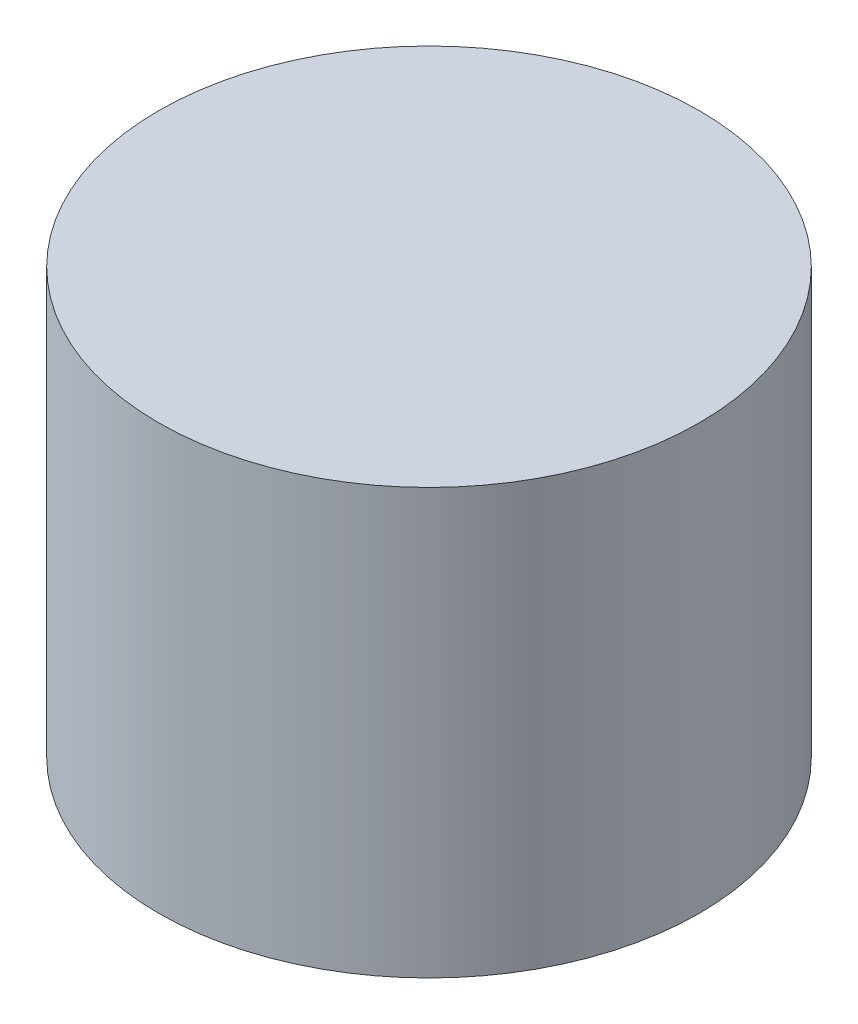
SolidWorks part; units mm, degrees
ref_plane "Front Plane" through (0, 0, 0) normal (0, 0, 1) x (1, 0, 0)
ref_plane "Top Plane" through (0, 0, 0) normal (0, 1, 0) x (1, 0, 0)
ref_plane "Right Plane" through (0, 0, 0) normal (1, 0, 0) x (0, 0, -1)
sketch "Sketch1" plane through (0, 0, 0) normal (0, 1, 0) x (1, 0, 0)
  circle A0 centre (0, 0) radius 35
  dimension "D1" = 70
extrude "Boss-Extrude1" add sketch "Sketch1" along normal blind 55
